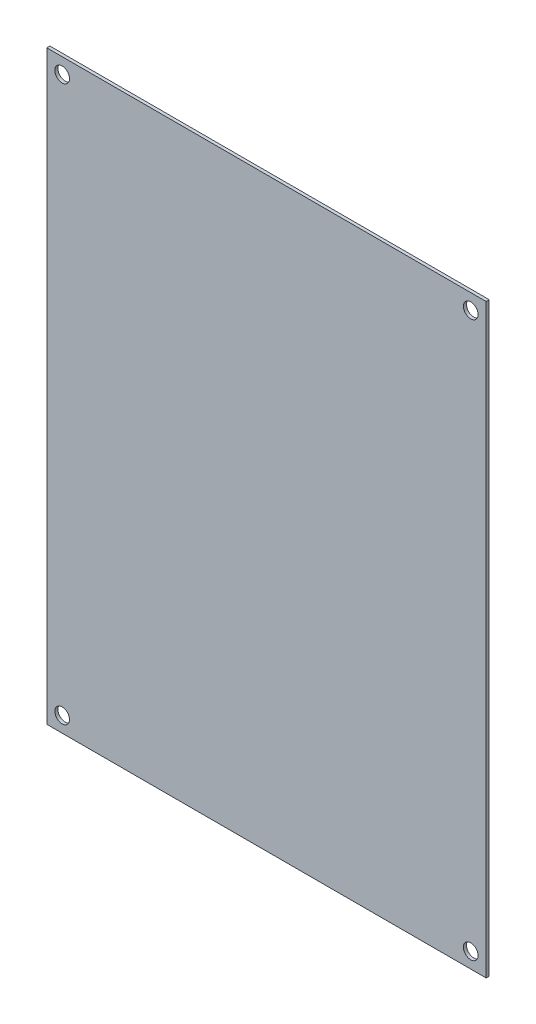
SolidWorks part; units mm, degrees
ref_plane "Alzado" through (0, 0, 0) normal (0, 0, 1) x (1, 0, 0)
ref_plane "Planta" through (0, 0, 0) normal (0, 1, 0) x (1, 0, 0)
ref_plane "Vista lateral" through (0, 0, 0) normal (1, 0, 0) x (0, 0, -1)
sketch "Croquis1" plane through (0, 0, 0) normal (0, 0, 1) x (1, 0, 0)
  line L0 (62.5, 5) -> (62.5, 431) construction
  line L3 (62.5, 431) -> (62.5, 218) construction
  line L4 (62.5, 218) -> (106.7661, 218) construction
  line L6 (-80, 408) -> (205, 408)
  line L7 (-80, 408) -> (-80, 28)
  line L8 (-80, 28) -> (205, 28)
  line L9 (205, 408) -> (205, 28)
  line L10 (-80, 408) -> (205, 28) construction
  line L11 (-80, 28) -> (205, 408) construction
  dimension "D1" = 285
  dimension "D2" = 380
extrude "Saliente-Extruir1" add sketch "Croquis1" along normal blind 2
sketch "Croquis2" plane through (0, 0, 2) normal (0, 0, 1) x (1, 0, 0)
  line L0 (-80, 218) -> (205, 218) construction
  line L1 (-80, 408) -> (-80, 28) construction
  line L2 (205, 28) -> (205, 408) construction
  line L3 (205, 218) -> (62.5, 218) construction
  line L4 (62.5, 218) -> (62.5, 408) construction
  line L5 (205, 408) -> (-80, 408) construction
  line L7 (-70, 398) -> (195, 398) construction
  line L8 (-70, 398) -> (-70, 38) construction
  line L9 (-70, 38) -> (195, 38) construction
  line L10 (195, 398) -> (195, 38) construction
  line L11 (-70, 398) -> (195, 38) construction
  line L12 (-70, 38) -> (195, 398) construction
  circle A0 centre (-70, 398) radius 4.7625
  circle A1 centre (195, 398) radius 4.7625
  circle A2 centre (195, 38) radius 4.7625
  circle A3 centre (-70, 38) radius 4.7625
  dimension "D3" = 9.525
  dimension "D1" = 10
  dimension "D2" = 10
extrude "Cortar-Extruir1" cut sketch "Croquis2" against normal blind 10
